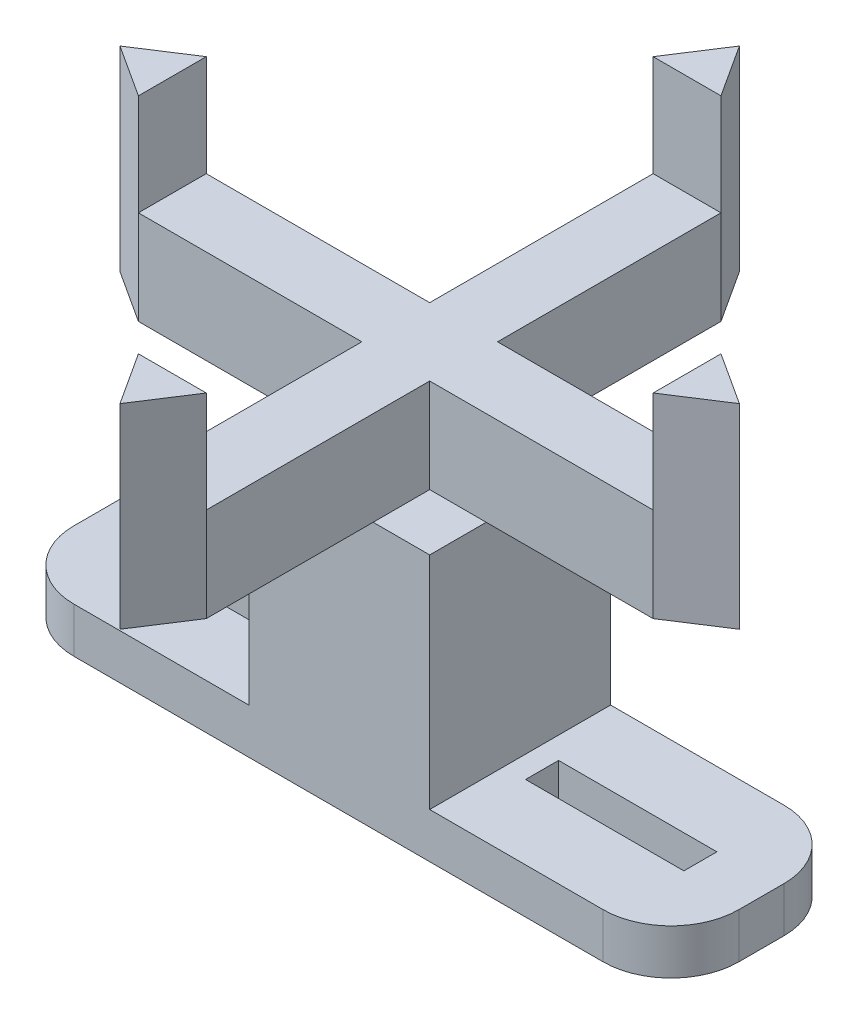
SolidWorks part; units mm, degrees
ref_plane "Front Plane" through (0, 0, 0) normal (0, 0, 1) x (1, 0, 0)
ref_plane "Top Plane" through (0, 0, 0) normal (0, 1, 0) x (1, 0, 0)
ref_plane "Right Plane" through (0, 0, 0) normal (1, 0, 0) x (0, 0, -1)
sketch "Sketch1" plane through (0, 0, 0) normal (0, 1, 0) x (1, 0, 0)
  line L0 (-68.059, -8.8969) -> (-61.059, -8.8969)
  line L7 (-67.759, -5.6269) -> (-44.359, -5.6269)
  line L10 (-70.759, -8.6269) -> (-70.759, -10.6269)
  line L11 (-67.759, -13.6269) -> (-44.359, -13.6269)
  line L12 (-41.359, -8.6269) -> (-41.359, -10.6269)
  line L17 (-51.059, -8.8969) -> (-44.059, -8.8969)
  line L18 (-51.059, -8.8969) -> (-51.059, -10.3569)
  line L19 (-51.059, -10.3569) -> (-44.059, -10.3569)
  line L20 (-44.059, -8.8969) -> (-44.059, -10.3569)
  line L21 (-68.059, -8.8969) -> (-68.059, -10.3569)
  line L22 (-68.059, -10.3569) -> (-61.059, -10.3569)
  line L23 (-61.059, -8.8969) -> (-61.059, -10.3569)
  arc A8 (-44.359, -5.6269) -> (-41.359, -8.6269) centre (-44.359, -8.6269) cw
  arc A9 (-44.359, -13.6269) -> (-41.359, -10.6269) centre (-44.359, -10.6269) ccw
  arc A10 (-70.759, -10.6269) -> (-67.759, -13.6269) centre (-67.759, -10.6269) ccw
  arc A11 (-67.759, -5.6269) -> (-70.759, -8.6269) centre (-67.759, -8.6269) ccw
  point P12 (-70.759, -9.6269)
  point P15 (-41.359, -5.6269)
  point P20 (-70.759, -13.6269)
  point P23 (-70.759, -5.6269)
  dimension "D1" = 2.7
  dimension "D2" = 8
  dimension "D3" = 29.4
  dimension "D9" = 3
  dimension "D4" = 7
  dimension "D5" = 1.46
  dimension "D6" = 2.7
  dimension "D7" = 3.27
  dimension "D8" = 3.27
extrude "Boss-Extrude2" add sketch "Sketch1" along normal blind 2
sketch "Sketch2" plane through (0, 2, 0) normal (0, 1, 0) x (1, 0, 0)
  line L21 (-44.359, -5.6269) -> (-67.759, -5.6269) construction
  line L22 (-60.0286, -5.6269) -> (-52.0286, -5.6269)
  line L23 (-60.0286, -5.6269) -> (-60.0286, -13.6269)
  line L24 (-60.0286, -13.6269) -> (-52.0286, -13.6269)
  line L25 (-52.0286, -5.6269) -> (-52.0286, -13.6269)
  line L26 (-67.759, -13.6269) -> (-44.359, -13.6269) construction
extrude "Boss-Extrude3" add sketch "Sketch2" along normal blind 9.7499
sketch "Sketch3" plane through (0, 11.7499, 0) normal (0, 1, 0) x (1, 0, 0)
  line L0 (-67.4086, -8.1269) -> (-57.5286, -8.1269)
  line L1 (-57.5286, -8.1269) -> (-57.5286, 1.7531)
  line L2 (-57.5286, 1.7531) -> (-54.5286, 1.7531)
  line L3 (-54.5286, 1.7531) -> (-54.5286, -8.1269)
  line L4 (-54.5286, -8.1269) -> (-44.6486, -8.1269)
  line L5 (-44.6486, -8.1269) -> (-44.6486, -11.1269)
  line L6 (-44.6486, -11.1269) -> (-54.5286, -11.1269)
  line L7 (-54.5286, -11.1269) -> (-54.5286, -21.0069)
  line L8 (-54.5286, -21.0069) -> (-57.5286, -21.0069)
  line L9 (-57.5286, -21.0069) -> (-57.5286, -11.1269)
  line L10 (-57.5286, -11.1269) -> (-67.4086, -11.1269)
  line L11 (-67.4086, -11.1269) -> (-67.4086, -8.1269)
  line L12 (-52.0286, -5.6269) -> (-60.0286, -5.6269) construction
  line L13 (-60.0286, -5.6269) -> (-60.0286, -13.6269) construction
  dimension "D1" = 3
  dimension "D2" = 9.88
  dimension "D3" = 2.5
  dimension "D4" = 2.5
extrude "Boss-Extrude4" add sketch "Sketch3" along normal blind 4.16
sketch "Sketch4" plane through (0, 11.7499, 0) normal (0, 1, 0) x (1, 0, 0)
  line L0 (-67.4086, -8.1269) -> (-69.7238, -9.6269)
  line L1 (-69.7238, -9.6269) -> (-67.4086, -11.1269)
  line L2 (-67.4086, -8.1269) -> (-67.4086, -11.1269) construction
  line L3 (-67.4086, -11.1269) -> (-67.4086, -8.1269)
  dimension "D1" = 2.3153
extrude "Boss-Extrude5" add sketch "Sketch4" along normal blind 8.6408
sketch "Sketch6" plane through (0, 0, 0) normal (0, 1, 0) x (1, 0, 0)
  line L0 (-44.6486, -8.1269) -> (-54.5286, -8.1269) construction
  line L1 (-54.5286, -13.6269) -> (-54.5286, -11.1269) construction
  circle A0 centre (-56.0286, -9.6269) radius 1.5
  dimension "D1" = 3
  dimension "D2" = 1.5
  dimension "D3" = 1.5
extrude "Boss-Extrude7" add sketch "Sketch6" along normal blind 0.5
pattern_circular "CirPattern2" count 4 over 360 about axis through (-56.0286, 0, 9.6269) along (0, 1, 0) of "Boss-Extrude5"
